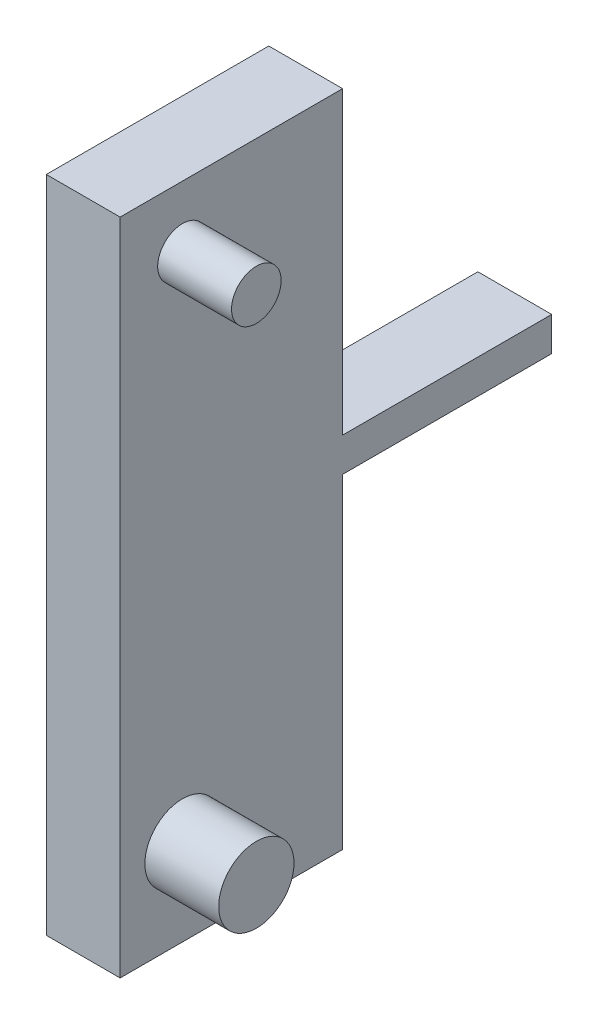
SolidWorks part; units mm, degrees
ref_plane "Front Plane" through (0, 0, 0) normal (1, 0, 0) x (0, 1, 0)
ref_plane "Top Plane" through (0, 0, 0) normal (0, 0, 1) x (0, 1, 0)
ref_plane "Right Plane" through (0, 0, 0) normal (0, 1, 0) x (-1, 0, 0)
sketch "Sketch1" plane through (0, 0, 0) normal (1, 0, 0) x (0, 1, 0)
  line L0 (-75.5543, 44.2382) -> (-40.9543, 44.2382) construction
  circle A0 centre (-40.9543, 44.2382) radius 2.55
  circle A1 centre (-75.5543, 44.2382) radius 2.55
  circle A2 centre (-75.5543, 44.2382) radius 1.68
  circle A3 centre (-40.9543, 44.2382) radius 1.68
  point P6 (-58.2543, 44.2382)
  dimension "D1" = 5.1
extrude "Boss-Extrude1" add sketch "Sketch1" along normal blind 10 contours A3 | A1
sketch "Sketch2" plane through (0, 0, 0) normal (1, 0, 0) x (0, 1, 0)
  line L0 (-75.5543, 44.2382) -> (-40.9543, 44.2382) construction
  line L1 (-81.4075, 48.4611) -> (-36.7832, 48.4611)
  line L2 (-81.4075, 48.4611) -> (-81.4075, 33.3968)
  line L3 (-81.4075, 33.3968) -> (-36.7832, 33.3968)
  line L4 (-36.7832, 48.4611) -> (-36.7832, 33.3968)
  line L5 (-59.4062, 44.2382) -> (-57.1024, 44.2382)
  line L6 (-59.4062, 44.2382) -> (-59.4062, 19.2382)
  line L7 (-59.4062, 19.2382) -> (-57.1024, 19.2382)
  line L8 (-57.1024, 44.2382) -> (-57.1024, 19.2382)
  dimension "D1" = 25
extrude "Boss-Extrude2" add sketch "Sketch2" along normal blind 5 contours L8 L3 L6 L7 | L8 L5 L6 L3 | L5 L8 L3 L4 L1 L2 L6
